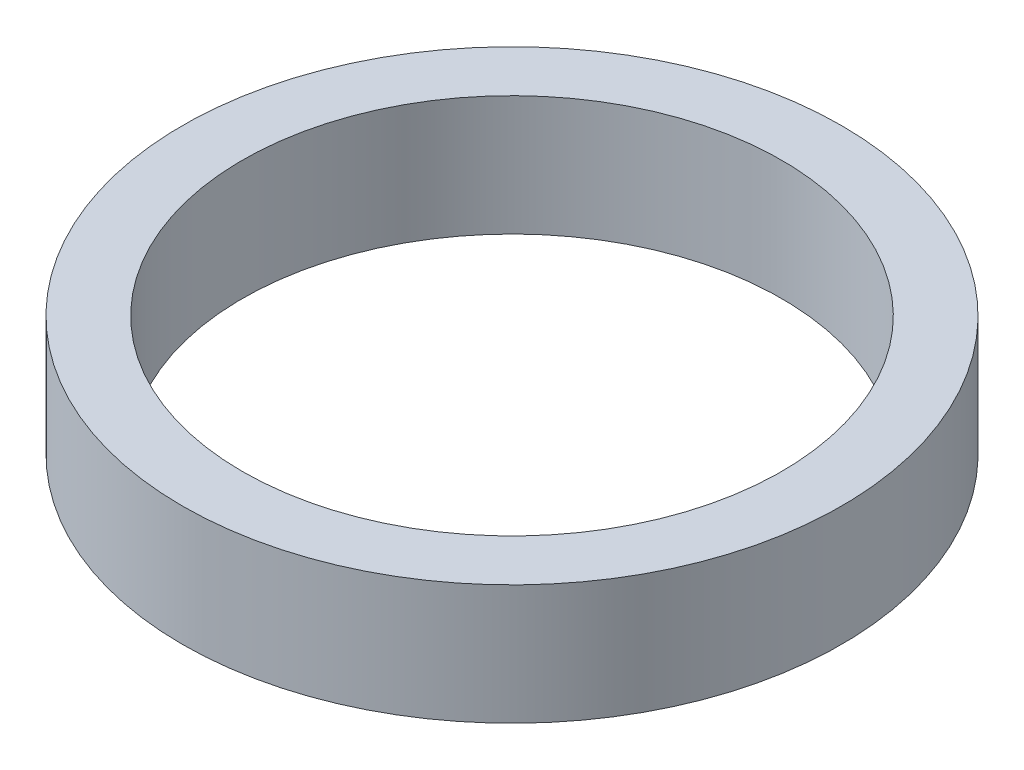
SolidWorks part; units mm, degrees
material "ABS"
ref_plane "Front Plane" through (0, 0, 0) normal (0, 0, 1) x (1, 0, 0)
ref_plane "Top Plane" through (0, 0, 0) normal (0, 1, 0) x (1, 0, 0)
ref_plane "Right Plane" through (0, 0, 0) normal (1, 0, 0) x (0, 0, -1)
sketch "Sketch1" plane through (0, 0, 0) normal (0, 1, 0) x (1, 0, 0)
  circle A0 centre (0, 0) radius 27.5
  circle A1 centre (0, 0) radius 22.5
  dimension "D1" = 55
  dimension "D2" = 45
extrude "Boss-Extrude1" add sketch "Sketch1" along normal mid plane 10
